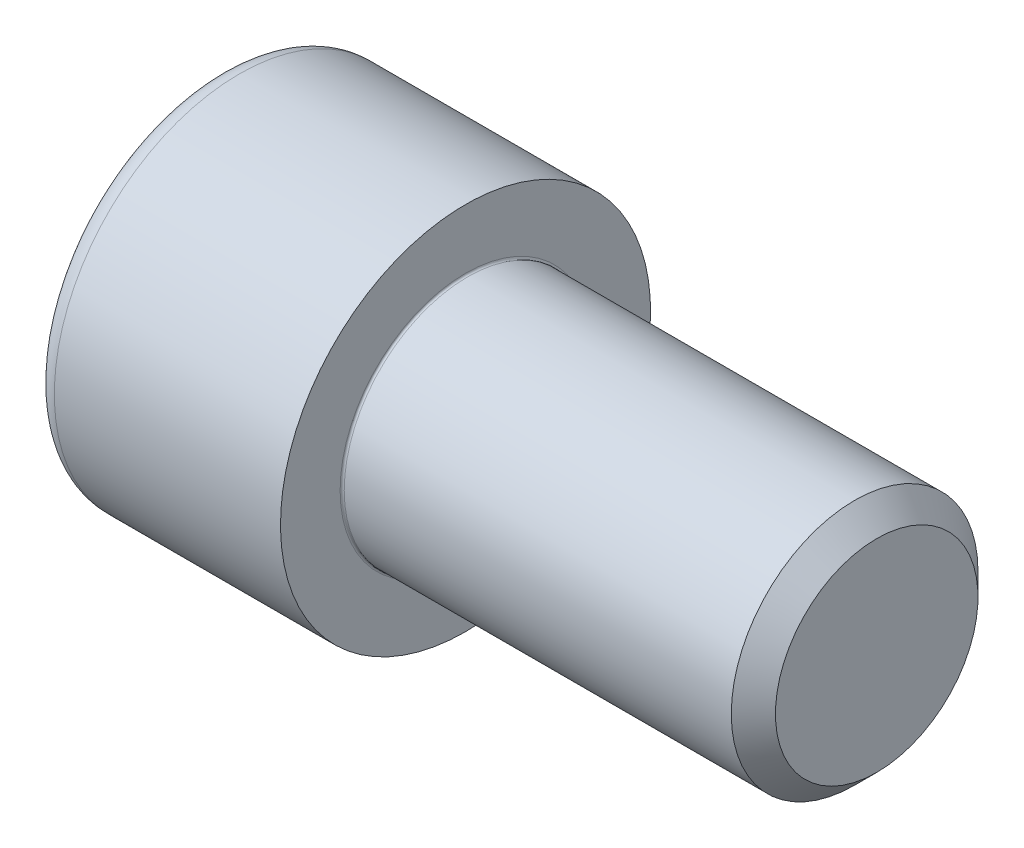
SolidWorks part; units mm, degrees
ref_plane "前基準面" through (0, 0, 0) normal (0, 0, 1) x (1, 0, 0)
ref_plane "上基準面" through (0, 0, 0) normal (0, 1, 0) x (1, 0, 0)
ref_plane "右基準面" through (0, 0, 0) normal (1, 0, 0) x (0, 0, -1)
ref_plane "平面1"
sketch "草圖1" plane through (0, 0, 0) normal (0, 0, 1) x (1, 0, 0)
  line L0 (-2.0667, 0) -> (20, 0)
  line L1 (20, 0) -> (20, 6)
  line L2 (20, 6) -> (4.3, 6)
  line L3 (4.3, 6) -> (3.2264, 6)
  line L4 (3.2264, 6) -> (0, 6)
  line L5 (0, 6) -> (0, 9)
  line L6 (0, 9) -> (-12, 9)
  line L7 (-12, 9) -> (-12, 5.7735)
  line L8 (-12, 5.7735) -> (-5.4, 5.7735)
  line L9 (-5.4, 5.7735) -> (-2.0667, 0)
  line L10 (-2.0667, 0) -> (20, 0) construction
  dimension "D1" = 90
  dimension "D2" = 1.0736
  dimension "D3" = 12
  dimension "D4" = 6.6
  dimension "D5" = 120
  dimension "D6" = 6
  dimension "D7" = 6
  dimension "D8" = 5.7735
  dimension "D9" = 9
revolve "本體" add sketch "草圖1" angle 360 about L10
cosmetic thread "裝飾螺紋線1" parameters "D1"=15.7, "D2"=10.072
ref_plane "平面2"
sketch "草圖2" plane through (-12, 0, 0) normal (-1, 0, 0) x (0, 0, 1)
  line L0 (5.7735, 0) -> (2.8868, -5)
  line L1 (2.8868, -5) -> (-2.8868, -5)
  line L2 (-2.8868, -5) -> (-5.7735, 0)
  line L3 (-5.7735, 0) -> (-2.8868, 5)
  line L4 (-2.8868, 5) -> (2.8868, 5)
  line L5 (2.8868, 5) -> (5.7735, 0)
  circle A0 centre (0, 0) radius 5.7735
extrude "塞槽" add sketch "草圖2" against normal up to next contours A0 | L0 L1 L2 L3 L4 L5
fillet "螺紋" radius 1 1 edges at (-12, -9, 0)
chamfer "倒角1" distance 1.0735 distance2 1.0735 1 edges at (20, -6, 0)
fillet "圓角2" radius 0.1 1 edges at (0, -6, 0)
